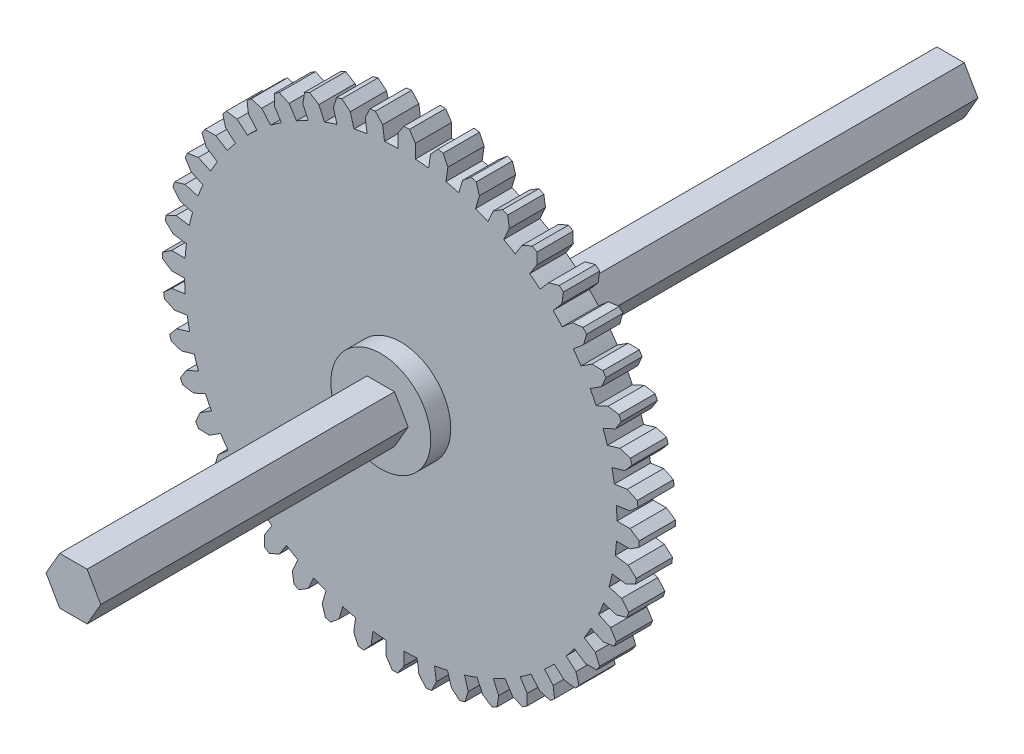
SolidWorks part; units mm, degrees
ref_plane "Front Plane" through (0, 0, 0) normal (0, 0, 1) x (1, 0, 0)
ref_plane "Top Plane" through (0, 0, 0) normal (0, 1, 0) x (1, 0, 0)
ref_plane "Right Plane" through (0, 0, 0) normal (1, 0, 0) x (0, 0, -1)
sketch "Sketch1" plane through (0, 0, 0) normal (0, 0, 1) x (1, 0, 0)
  circle A0 centre (0, 0) radius 8.65
  dimension "D1" = 17.3
extrude "Boss-Extrude1" add sketch "Sketch1" along normal blind 1.45
sketch "Sketch2" plane through (0, 0, 1.45) normal (0, 0, 1) x (1, 0, 0)
  circle A0 centre (0, 0) radius 2
  dimension "D1" = 4
extrude "Boss-Extrude3" add sketch "Sketch2" along normal blind 0.8
sketch "Sketch3" plane through (0, 0, 2.25) normal (0, 0, 1) x (1, 0, 0)
  line L1 (-1.097, 0) -> (-0.5485, -0.95)
  line L2 (-0.5485, -0.95) -> (0.5485, -0.95)
  line L3 (0.5485, -0.95) -> (1.097, 0)
  line L4 (1.097, 0) -> (0.5485, 0.95)
  line L5 (0.5485, 0.95) -> (-0.5485, 0.95)
  line L6 (-0.5485, 0.95) -> (-1.097, 0)
  circle A0 centre (0, 0) radius 0.95 construction
extrude "Boss-Extrude4" add sketch "Sketch3" along normal blind 12.3 and the other way blind 22.8
sketch "Sketch4" plane through (0, 0, 1.45) normal (0, 0, 1) x (1, 0, 0)
  line L1 (-0.1187, 8.6229) -> (-0.1187, 9.1734)
  line L2 (0.1252, 9.5385) -> (0.3437, 9.5385)
  line L3 (-0.1187, 9.1734) -> (0.1252, 9.5385)
  line L4 (0.3437, 9.5385) -> (0.5844, 9.1734)
  line L5 (0.5844, 9.1734) -> (0.5844, 8.6051)
  line L6 (0.5844, 8.6051) -> (-0.1187, 8.6229)
extrude "Boss-Extrude7" add sketch "Sketch4" against normal blind 1.45
pattern_circular "CirPattern2" count 44 over 360 about axis through (0, 0, 0) along (0, 0, 1) of "Boss-Extrude7"
